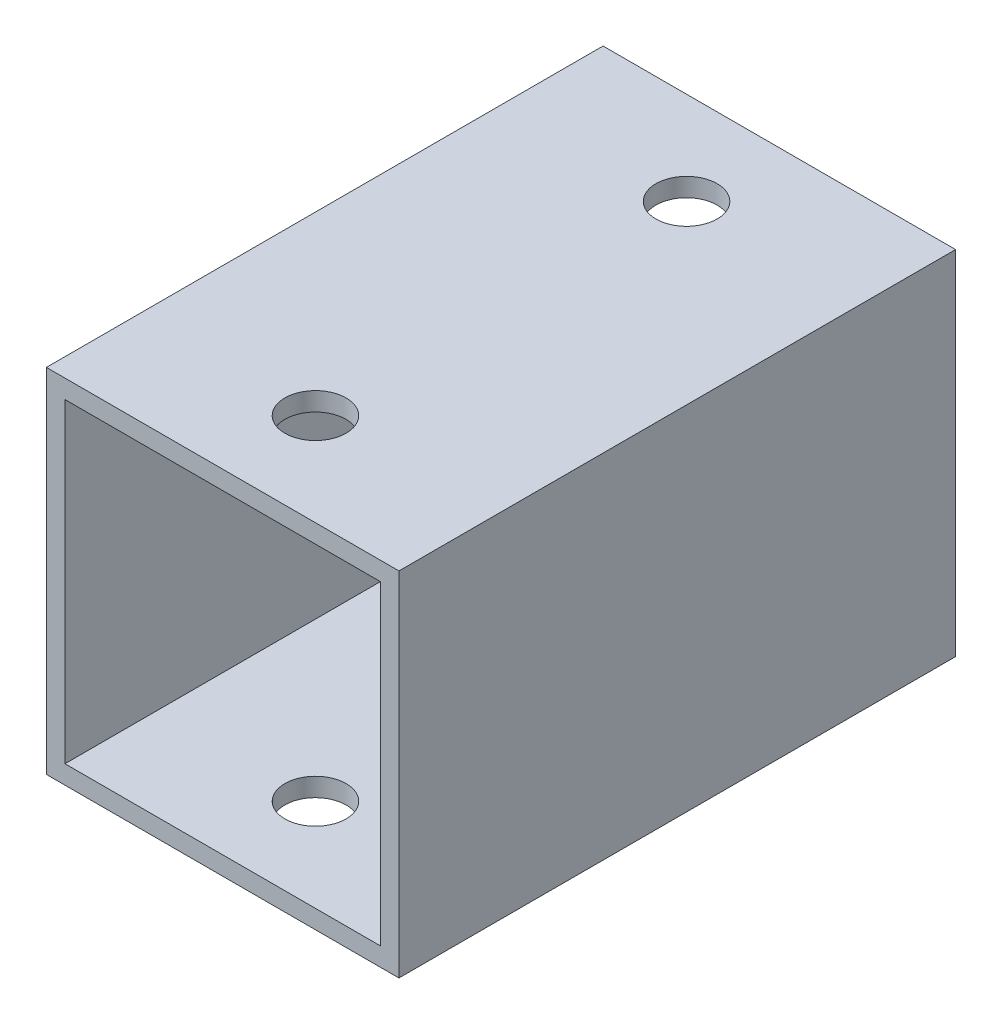
SolidWorks part; units mm, degrees
ref_plane "Plano frontal" through (0, 0, 0) normal (0, 0, 1) x (1, 0, 0)
ref_plane "Plano superior" through (0, 0, 0) normal (0, 1, 0) x (1, 0, 0)
ref_plane "Plano direito" through (0, 0, 0) normal (1, 0, 0) x (0, 0, -1)
sketch "Esboço1" plane through (0, 0, 0) normal (0, 0, 1) x (1, 0, 0)
  line L1 (0, 0) -> (19, 0)
  line L2 (0, 0) -> (0, 19)
  line L3 (0, 19) -> (19, 19)
  line L4 (19, 0) -> (19, 19)
  dimension "D1" = 19
extrude "Ressalto-extrusão1" add sketch "Esboço1" along normal blind 30
shell "Casca1" thickness 1
sketch "Esboço2" plane through (0, 19, 0) normal (0, 1, 0) x (1, 0, 0)
  line L0 (19, 0) -> (0, 0) construction
  line L1 (19, -30) -> (0, -30) construction
  circle A1 centre (9.5, -25) radius 1.65
  circle A6 centre (9.5, -5) radius 1.65
  point P2 (9.5, 0)
  point P4 (0, 0)
  dimension "D1" = 3.3
  dimension "D2" = 5
  dimension "D3" = 5
extrude "Corte-extrusão1" cut sketch "Esboço2" against normal through all
